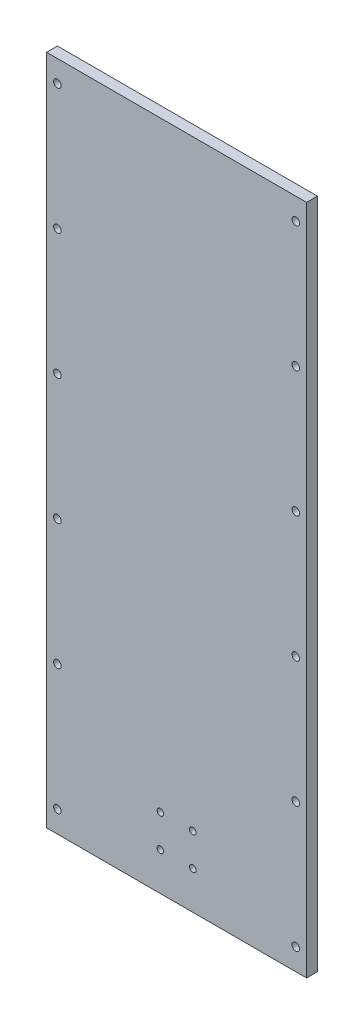
SolidWorks part; units mm, degrees
ref_plane "Plan de face" through (0, 0, 0) normal (0, 0, 1) x (1, 0, 0)
ref_plane "Plan de dessus" through (0, 0, 0) normal (0, 1, 0) x (1, 0, 0)
ref_plane "Plan de droite" through (0, 0, 0) normal (1, 0, 0) x (0, 0, -1)
sketch "Esquisse1" plane through (0, 0, 0) normal (0, 0, 1) x (1, 0, 0)
  line L1 (60, -155) -> (-60, -155)
  line L2 (60, -155) -> (60, 155)
  line L3 (60, 155) -> (-60, 155)
  line L4 (-60, -155) -> (-60, 155)
  line L5 (60, -155) -> (-60, 155) construction
  line L6 (60, 155) -> (-60, -155) construction
  point P0 (0, 0)
  dimension "D1" = 310
  dimension "D2" = 120
extrude "Boss.-Extru.1" add sketch "Esquisse1" along normal blind 5
sketch "Esquisse2" plane through (0, 0, 5) normal (0, 0, 1) x (1, 0, 0)
  line L0 (60, 155) -> (-60, 155) construction
  line L2 (-55, 145) -> (60, 145) construction
  line L3 (60, -155) -> (60, 155) construction
  line L4 (-55, 145) -> (-55, -155) construction
  line L5 (-60, -155) -> (60, -155) construction
  line L6 (-7.5, -122.5) -> (7.5, -122.5) construction
  line L7 (0, 0) -> (0, -155) construction
  line L8 (7.5, -142.5) -> (-7.5, -142.5) construction
  line L9 (12.5, -137.5) -> (12.5, -122.5) construction
  line L10 (7.5, -117.5) -> (-7.5, -117.5) construction
  line L11 (-12.5, -137.5) -> (-12.5, -122.5) construction
  line L12 (12.5, -142.5) -> (-12.5, -117.5) construction
  line L13 (12.5, -117.5) -> (-12.5, -142.5) construction
  line L14 (-7.5, -122.5) -> (-7.5, -137.5) construction
  line L15 (55, 145) -> (55, -155) construction
  circle A0 centre (-55, 145) radius 1.7476
  circle A2 centre (55, 145) radius 1.7476
  circle A3 centre (-55, 87) radius 1.7476
  circle A4 centre (-55, 29) radius 1.7476
  circle A5 centre (-55, -29) radius 1.7476
  circle A6 centre (-55, -87) radius 1.7476
  circle A11 centre (55, 87) radius 1.7476
  circle A12 centre (55, 29) radius 1.7476
  circle A13 centre (55, -29) radius 1.7476
  circle A14 centre (55, -87) radius 1.7476
  circle A15 centre (0, -130) radius 4.5 construction
  arc A16 (7.5, -142.5) -> (12.5, -137.5) centre (7.5, -137.5) ccw construction
  arc A17 (-7.5, -142.5) -> (-12.5, -137.5) centre (-7.5, -137.5) cw construction
  arc A18 (12.5, -122.5) -> (7.5, -117.5) centre (7.5, -122.5) ccw construction
  arc A19 (-7.5, -117.5) -> (-12.5, -122.5) centre (-7.5, -122.5) ccw construction
  circle A20 centre (-7.5, -122.5) radius 1.5
  circle A21 centre (7.5, -122.5) radius 1.5
  circle A22 centre (7.5, -137.5) radius 1.5
  circle A23 centre (-7.5, -137.5) radius 1.5
  circle A24 centre (55, -145) radius 1.7476
  circle A25 centre (0, 145) radius 1.7476 [skipped]
  circle A26 centre (-55, -145) radius 1.7476
  dimension "D8" = 9
  dimension "D10" = 5
  dimension "D12" = 3
  dimension "D1" = 10
  dimension "D2" = 10
  dimension "D4" = 5
  dimension "D6" = 10
  dimension "D9" = 25
  dimension "D11" = 25
  dimension "D3" = 3
  dimension "D5" = 6
  dimension "D13" = 2
  dimension "D14" = 2
extrude "Enlèv. mat.-Extru.1" cut sketch "Esquisse2" against normal blind 10
